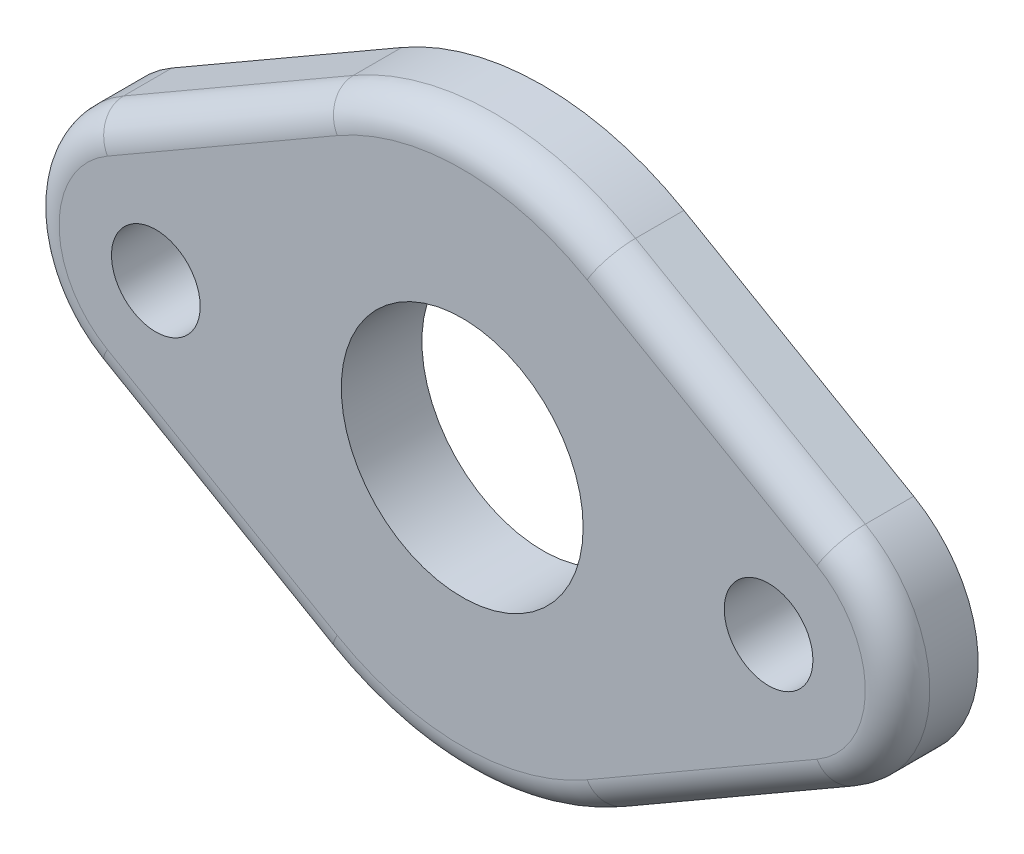
SolidWorks part; units mm, degrees
ref_plane "前基準面" through (0, 0, 0) normal (0, 0, 1) x (1, 0, 0)
ref_plane "上基準面" through (0, 0, 0) normal (0, 1, 0) x (1, 0, 0)
ref_plane "右基準面" through (0, 0, 0) normal (1, 0, 0) x (0, 0, -1)
sketch "草圖1" plane through (0, 0, 0) normal (0, 0, 1) x (1, 0, 0)
  line L4 (-8.75, 100.1554) -> (-23, 91.9282)
  line L5 (-23, 78.0718) -> (-8.75, 69.8446)
  line L6 (8.75, 69.8446) -> (23, 78.0718)
  line L7 (23, 91.9282) -> (8.75, 100.1554)
  line L8 (-8.75, 100.1554) -> (-23, 91.9282)
  line L9 (-23, 78.0718) -> (-8.75, 69.8446)
  line L10 (8.75, 69.8446) -> (23, 78.0718)
  line L11 (23, 91.9282) -> (8.75, 100.1554)
  circle A0 centre (19, 85) radius 2.75
  circle A1 centre (0, 85) radius 7.5
  circle A2 centre (-19, 85) radius 2.75
  arc A4 (8.75, 100.1554) -> (-8.75, 100.1554) centre (0, 85) ccw
  arc A5 (-23, 91.9282) -> (-23, 78.0718) centre (-19, 85) ccw
  arc A6 (-8.75, 69.8446) -> (8.75, 69.8446) centre (0, 85) ccw
  arc A7 (23, 78.0718) -> (23, 91.9282) centre (19, 85) ccw
  arc A8 (8.75, 100.1554) -> (-8.75, 100.1554) centre (0, 85) ccw
  arc A9 (-23, 91.9282) -> (-23, 78.0718) centre (-19, 85) ccw
  arc A10 (-8.75, 69.8446) -> (8.75, 69.8446) centre (0, 85) ccw
  arc A11 (23, 78.0718) -> (23, 91.9282) centre (19, 85) ccw
  dimension "D2" = 5.5
  dimension "D3" = 15
  dimension "D1" = 0
extrude "填料-伸長1" add sketch "草圖1" along normal blind 5
fillet "圓角1" radius 2 8 edges at (15.875, 96.0418, 5) (27, 85, 5) (15.875, 73.9582, 5) (0, 67.5, 5) (-15.875, 73.9582, 5) (-27, 85, 5) (-15.875, 96.0418, 5) (0, 102.5, 5)
